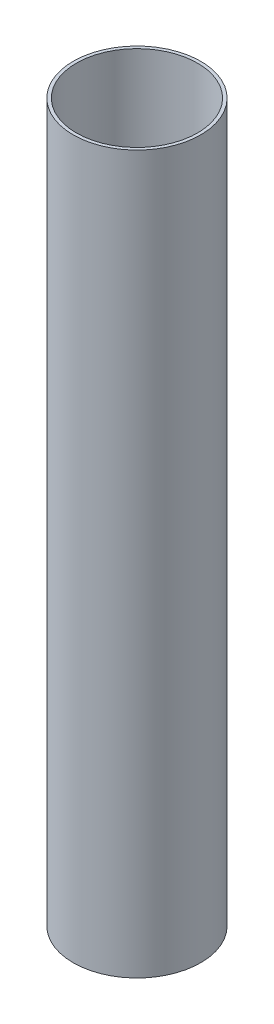
SolidWorks part; units mm, degrees
ref_plane "Front Plane" through (0, 0, 0) normal (0, 0, 1) x (1, 0, 0)
ref_plane "Top Plane" through (0, 0, 0) normal (0, 1, 0) x (1, 0, 0)
ref_plane "Right Plane" through (0, 0, 0) normal (1, 0, 0) x (0, 0, -1)
sketch "Sketch1" plane through (0, 0, 0) normal (0, 1, 0) x (1, 0, 0)
  circle A0 centre (0, 0) radius 31.25
  circle A1 centre (0, 0) radius 32.9
  dimension "D1" = 65.8
  dimension "D2" = 62.5
extrude "Boss-Extrude1" add sketch "Sketch1" along normal mid plane 370
